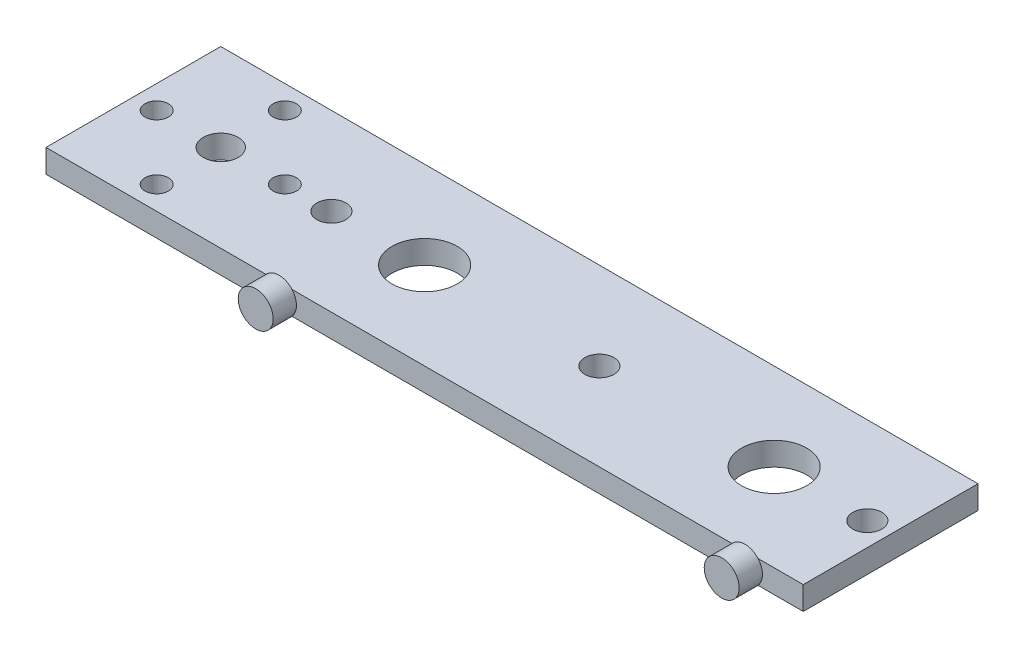
SolidWorks part; units mm, degrees
ref_plane "前视基准面" through (0, 0, 0) normal (0, 0, 1) x (1, 0, 0)
ref_plane "上视基准面" through (0, 0, 0) normal (0, 1, 0) x (1, 0, 0)
ref_plane "右视基准面" through (0, 0, 0) normal (1, 0, 0) x (0, 0, -1)
other "Configuration Table"
sketch "草图1" plane through (0, 0, 0) normal (0, 1, 0) x (1, 0, 0)
  line L0 (0, 7.5) -> (0, -7.5) construction
  line L1 (-25, 7.5) -> (25, 7.5)
  line L2 (-25, 7.5) -> (-25, -7.5)
  line L3 (-25, -7.5) -> (25, -7.5)
  line L4 (25, 7.5) -> (25, -7.5)
  line L5 (-25, 0) -> (25, 0) construction
  line L7 (-25, -7.5) -> (-40, -7.5)
  line L10 (-25, -7.5) -> (-25, 7.5)
  line L11 (-25, 7.5) -> (-40, 7.5)
  line L12 (-40, -7.5) -> (-40, 7.5)
  line L14 (-25, 7.5) -> (-40, 7.5)
  dimension "D1" = 50
  dimension "D2" = 15
  dimension "D6" = 15
  dimension "D7" = 15
extrude "凸台-拉伸1" add sketch "草图1" along normal blind 2
sketch "草图2" plane through (0, 0, 0) normal (0, 1, 0) x (1, 0, 0)
  line L0 (0, 7.5) -> (0, -7.5) construction
  line L1 (25, 7.5) -> (-40, 7.5) construction
  line L2 (-32.5, 7.5) -> (-32.5, -7.5) construction
  line L3 (-40, -7.5) -> (-40, 7.5) construction
  line L4 (-25, 7.5) -> (-25, -7.5) construction
  line L6 (-25, -7.5) -> (25, -7.5) construction
  line L10 (-40, 0) -> (-25, 0) construction
  line L14 (-40, -7.5) -> (25, -7.5) construction
  circle A2 centre (0, 0) radius 1.25
  circle A3 centre (15, 0) radius 4.1
  circle A4 centre (15, 0) radius 2.8
  circle A5 centre (-15, 0) radius 4.1
  circle A6 centre (-15, 0) radius 2.8
  circle A8 centre (23, 0) radius 1.25
  circle A9 centre (-23, 0) radius 1.25
  circle A11 centre (-32.5, 0) radius 1.5
  circle A12 centre (-27, 0) radius 1
  circle A13 centre (-32.5, -5.5) radius 1
  circle A14 centre (-38, 0) radius 1
  circle A15 centre (-32.5, 5.5) radius 1
  point P36 (0, -7.5)
  dimension "D3" = 2.5
  dimension "D4" = 5.6
  dimension "D5" = 8.2
  dimension "D7" = 15
  dimension "D8" = 2.5
  dimension "D11" = 3
  dimension "D12" = 2
  dimension "D2" = 7.5
  dimension "D6" = 15
  dimension "D10" = 8
  dimension "D13" = 5.5
  dimension "D17" = 7.5
  dimension "D14" = 4
extrude "切除-拉伸1" cut sketch "草图2" along normal up to surface (2 mm away)
sketch "草图4" plane through (0, 0, 7.5) normal (0, 0, 1) x (1, 0, 0)
  line L0 (25, 1) -> (-40, 1) construction
  line L1 (25, 2) -> (25, 0) construction
  line L2 (-40, 2) -> (-40, 0) construction
  line L3 (0, 0) -> (0, 2) construction
  line L5 (25, 2) -> (25, 0) construction
  line L6 (-40, 2) -> (25, 2) construction
  circle A0 centre (20, 1) radius 1.5
  circle A1 centre (-20, 1) radius 1.5
  dimension "D1" = 3
  dimension "D2" = 3
  dimension "D3" = 20
  dimension "D4" = 20
  dimension "D5" = 25
extrude "凸台-拉伸2" add sketch "草图4" along normal blind 2
